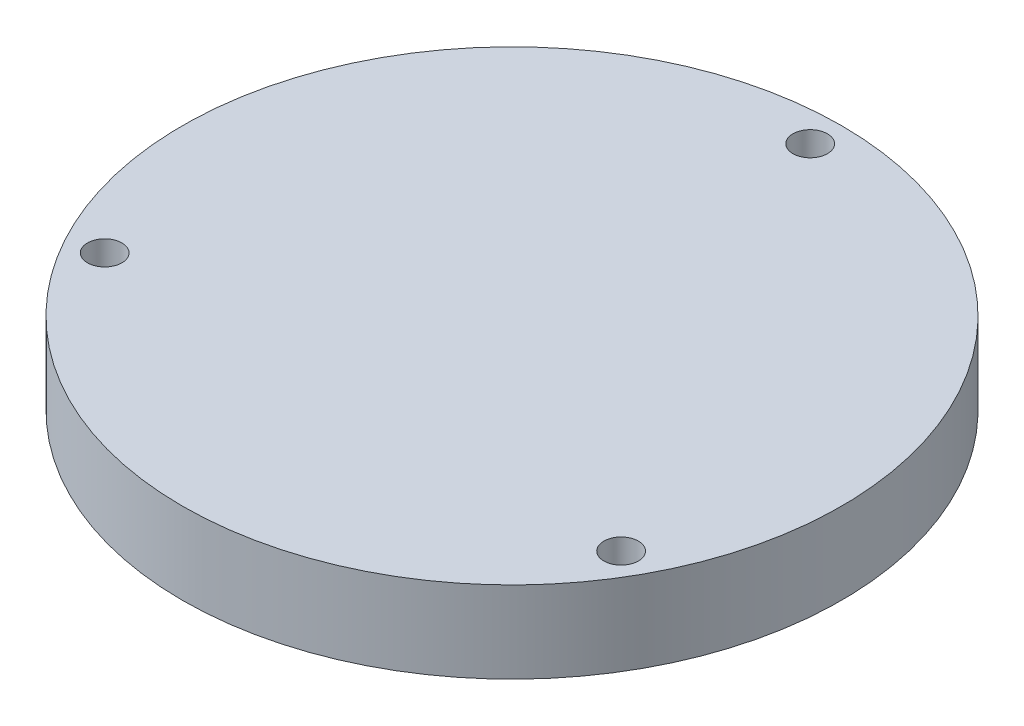
SolidWorks part; units mm, degrees
ref_plane "Plan de face" through (0, 0, 0) normal (0, 0, 1) x (1, 0, 0)
ref_plane "Plan de dessus" through (0, 0, 0) normal (0, 1, 0) x (1, 0, 0)
ref_plane "Plan de droite" through (0, 0, 0) normal (1, 0, 0) x (0, 0, -1)
sketch "Esquisse1" plane through (0, 0, 0) normal (0, 1, 0) x (1, 0, 0)
  line L0 (0, 55.0784) -> (0, -55.7052) construction
  line L1 (-4, 47.5) -> (-4, 50.3413) construction
  line L2 (4, 47.5) -> (4, 50.3413) construction
  line L3 (0, 0) -> (68.6571, 39.6392) construction
  line L4 (0, 0) -> (-63.5298, 36.6789) construction
  line L5 (-4, 48.1274) -> (-4, 47.5)
  line L6 (4, 48.1274) -> (4, 47.5)
  line L7 (43.6796, -20.5996) -> (43.1362, -20.2859)
  line L8 (39.6796, -27.5278) -> (39.1362, -27.2141)
  line L9 (-39.6796, -27.5278) -> (-39.1362, -27.2141)
  line L10 (-43.6796, -20.5996) -> (-43.1362, -20.2859)
  circle A0 centre (0, 0) radius 52.5
  circle A1 centre (0, 0) radius 50.5 construction
  circle A2 centre (0, 47.5) radius 4
  arc A3 (6.2474, 50.1121) -> (43.7343, 25.25) centre (0, 0) cw
  arc A4 (-6.2474, 50.1121) -> (-43.7343, 25.25) centre (0, 0) ccw
  arc A5 (4, 48.1274) -> (6.2474, 50.1121) centre (6, 48.1274) cw
  arc A6 (-4, 48.1274) -> (-6.2474, 50.1121) centre (-6, 48.1274) ccw
  arc A7 (46.522, -19.6456) -> (43.7343, 25.25) centre (0, 0) ccw
  circle A8 centre (41.1362, -23.75) radius 4
  arc A9 (40.2746, -30.4665) -> (0, -50.5) centre (0, 0) cw
  arc A10 (39.6796, -27.5278) -> (40.2746, -30.4665) centre (38.6796, -29.2599) cw
  arc A11 (43.6796, -20.5996) -> (46.522, -19.6456) centre (44.6796, -18.8676) ccw
  arc A12 (-40.2746, -30.4665) -> (0, -50.5) centre (0, 0) ccw
  circle A13 centre (-41.1362, -23.75) radius 4
  arc A14 (-46.522, -19.6456) -> (-43.7343, 25.25) centre (0, 0) cw
  arc A15 (-43.6796, -20.5996) -> (-46.522, -19.6456) centre (-44.6796, -18.8676) cw
  arc A16 (-39.6796, -27.5278) -> (-40.2746, -30.4665) centre (-38.6796, -29.2599) ccw
  point P49 (0, 0)
  dimension "D1" = 105
  dimension "D2" = 2
  dimension "D3" = 2
  dimension "D4" = 8
  dimension "D5" = 47.5
  dimension "D6" = 60
  dimension "D7" = 60
  dimension "D8" = 3
extrude "Boss.-Extru.1" add sketch "Esquisse1" along normal blind 10 contours A0 A16 L9 A13 L10 A15 A14 A4 A6 L5 A2 L6 A5 A3 A7 A11 L7 A8 L8 A10 A9 A12 | A13 | A8 | A2 A9
sketch "Esquisse2" plane through (0, 10, 0) normal (0, 1, 0) x (1, 0, 0)
  circle A1 centre (0, 0) radius 52.5
  circle A2 centre (0, 0) radius 52.5
  dimension "D1" = 0
extrude "Boss.-Extru.2" add sketch "Esquisse2" along normal blind 3
sketch "Esquisse3" plane through (0, 0, 0) normal (0, -1, 0) x (1, 0, 0)
  circle A0 centre (0, -47.5) radius 2.75
  circle A1 centre (0, 0) radius 52.5
  circle A2 centre (0, 0) radius 52.5
  circle A3 centre (-41.1362, 23.75) radius 2.75
  circle A4 centre (41.1362, 23.75) radius 2.75
  point P13 (0, 0)
  dimension "D2" = 5.5
  dimension "D1" = 0
  dimension "D3" = 3
extrude "Enlèv. mat.-Extru.2" cut sketch "Esquisse3" against normal through all from offset 3 contours A4 | A3 | A0 offset against normal yes
sketch "Esquisse4" plane through (0, 0, 0) normal (0, -1, 0) x (1, 0, 0)
  arc A0 (4, -47.5) -> (-4, -47.5) centre (0, -47.5) ccw construction
  arc A1 (4, -47.5) -> (-4, -47.5) centre (0, -47.5) ccw
  circle A2 centre (0, -47.5) radius 1.55
  circle A3 centre (-41.1362, 23.75) radius 1.55
  circle A4 centre (41.1362, 23.75) radius 1.55
  point P11 (0, 0)
  dimension "D1" = 3
  dimension "D2" = 3.1
extrude "Enlèv. mat.-Extru.3" cut sketch "Esquisse4" against normal through all contours A2 | A3 | A4
sketch "Esquisse5" plane through (0, 13, 0) normal (0, 1, 0) x (1, 0, 0)
  line L0 (-57.8947, 998.3227) -> (0, 0)
  line L1 (0, 0) -> (57.8947, 998.3227)
  line L2 (-57.8947, 998.3227) -> (57.8947, 998.3227)
  line L3 (893.5202, -449.023) -> (835.6254, -549.2997)
  line L4 (0, 0) -> (835.6254, -549.2997)
  line L5 (893.5202, -449.023) -> (0, 0)
  line L6 (-835.6254, -549.2997) -> (-893.5202, -449.023)
  line L7 (0, 0) -> (-893.5202, -449.023)
  line L8 (-835.6254, -549.2997) -> (0, 0)
  circle A0 centre (0, 0) radius 1000 construction
  circle A1 centre (0, 47.5) radius 2.75 construction
  circle A2 centre (0, 0) radius 52.5
  circle A3 centre (0, 0) radius 52.5
  circle A4 centre (0, 47.5) radius 2.75 construction
  point P19 (0, 0)
  dimension "D1" = 0
  dimension "D2" = 2000
  dimension "D3" = 115.7895
  dimension "D4" = 3
  dimension "D5" = 6.638
